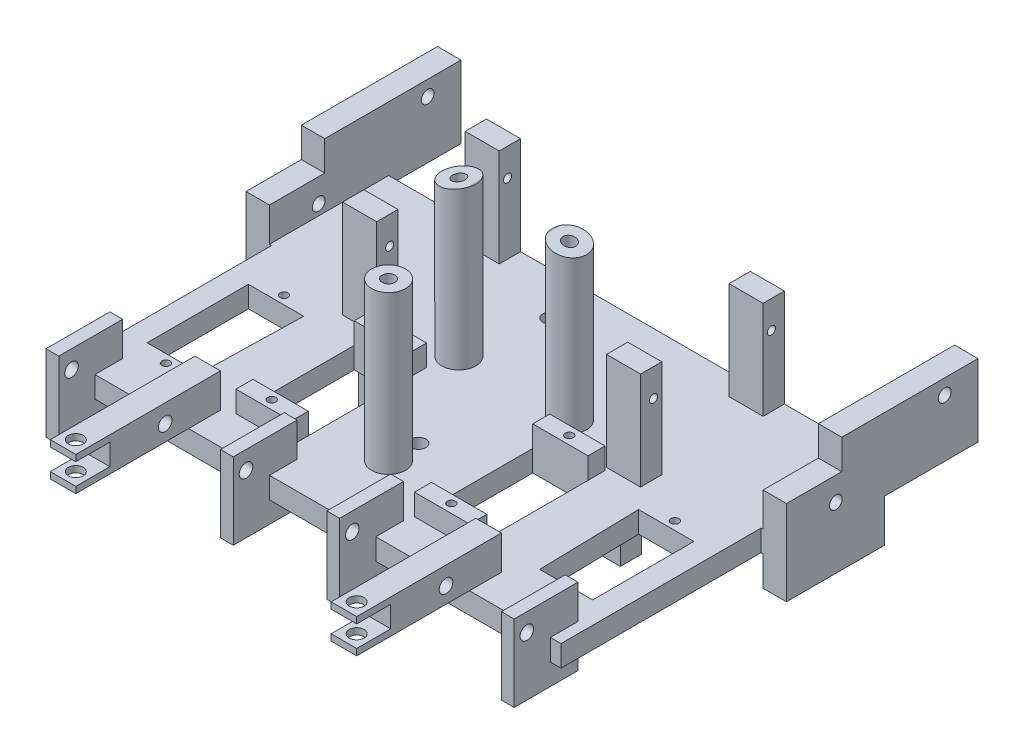
SolidWorks part; units mm, degrees
material "PMMA"
ref_plane "前视基准面" through (0, 0, 0) normal (0, 0, 1) x (1, 0, 0)
ref_plane "上视基准面" through (0, 0, 0) normal (0, 1, 0) x (1, 0, 0)
ref_plane "右视基准面" through (0, 0, 0) normal (1, 0, 0) x (0, 0, -1)
sketch "草图1" plane through (0, 0, 0) normal (0, 1, 0) x (1, 0, 0)
  line L1 (-57.5, 37.5) -> (57.5, 37.5)
  line L2 (-57.5, 37.5) -> (-57.5, -37.5)
  line L3 (-57.5, -37.5) -> (57.5, -37.5)
  line L4 (57.5, 37.5) -> (57.5, -37.5)
  line L5 (-57.5, 37.5) -> (57.5, -37.5) construction
  line L6 (-57.5, -37.5) -> (57.5, 37.5) construction
  point P0 (0, 0)
  dimension "D1" = 115
  dimension "D2" = 75
extrude "凸台-拉伸1" add sketch "草图1" along normal blind 5
sketch "草图4" plane through (0, 5, 0) normal (0, 1, 0) x (1, 0, 0)
  line L1 (-58, 9.5) -> (58, 9.5)
  line L2 (-58, 9.5) -> (-58, 37.5)
  line L3 (-58, 37.5) -> (58, 37.5)
  line L4 (58, 9.5) -> (58, 37.5)
  line L5 (-58, 9.5) -> (58, 37.5) construction
  line L6 (-58, 37.5) -> (58, 9.5) construction
  line L7 (-57.5, -37.5) -> (57.5, -37.5) construction
  point P0 (0, 23.5)
  dimension "D1" = 116
  dimension "D2" = 28
  dimension "D3" = 75
extrude "凸台-拉伸4" add sketch "草图4" against normal blind 5
sketch "草图5" plane through (-58, 0, 0) normal (-1, 0, 0) x (0, 0, 1)
  line L0 (-37.5, 5) -> (-9.5, 5) construction
  line L1 (-9.5, 13) -> (-32.5, 13)
  line L2 (-9.5, 13) -> (-9.5, -7)
  line L3 (-9.5, -7) -> (-32.5, -7)
  line L4 (-32.5, 13) -> (-32.5, -7)
  line L5 (-9.5, 5) -> (-9.5, 0) construction
  dimension "D1" = 8
  dimension "D2" = 23
  dimension "D3" = 20
extrude "凸台-拉伸5" add sketch "草图5" along normal blind 5.5
sketch "草图6" plane through (-58, 0, 0) normal (-1, 0, 0) x (0, 0, 1)
  line L1 (-54.5, 20) -> (-22.5, 20)
  line L2 (-54.5, 20) -> (-54.5, 3)
  line L3 (-54.5, 3) -> (-22.5, 3)
  line L4 (-22.5, 20) -> (-22.5, 3)
  line L5 (-37.5, 5) -> (-32.5, 5) construction
  line L6 (-37.5, 0) -> (-37.5, 5) construction
  dimension "D1" = 15
  dimension "D2" = 17
  dimension "D3" = 32
  dimension "D4" = 17
extrude "凸台-拉伸6" add sketch "草图6" along normal blind 5.5
sketch "草图8" plane through (0, 5, 0) normal (0, 1, 0) x (1, 0, 0)
  line L0 (58, 37.5) -> (-58, 37.5) construction
  line L1 (-35, 37.5) -> (-27, 37.5)
  line L2 (-35, 37.5) -> (-35, 32.5)
  line L3 (-35, 32.5) -> (-27, 32.5)
  line L4 (-27, 37.5) -> (-27, 32.5)
  line L6 (-35, 8.7) -> (-27, 8.7)
  line L7 (-35, 8.7) -> (-35, 3.7)
  line L8 (-35, 3.7) -> (-27, 3.7)
  line L9 (-27, 8.7) -> (-27, 3.7)
  dimension "D1" = 23.8
  dimension "D2" = 35
  dimension "D3" = 8
  dimension "D4" = 5
  dimension "D5" = 5
extrude "凸台-拉伸7" add sketch "草图8" along normal blind 23
sketch "草图9" plane through (0, 5, 0) normal (0, 1, 0) x (1, 0, 0)
  line L1 (-14, -31) -> (-11, -31)
  line L2 (-14, -31) -> (-14, -46)
  line L3 (-14, -46) -> (-11, -46)
  line L4 (-11, -31) -> (-11, -46)
  dimension "D1" = 14
  dimension "D2" = 3
  dimension "D3" = 15
  dimension "D4" = 46
extrude "凸台-拉伸8" add sketch "草图9" along normal blind 8 and the other way blind 10
sketch "草图10" plane through (0, 5, 0) normal (0, 1, 0) x (1, 0, 0)
  line L0 (-14, -31) -> (-14, -46) construction
  line L1 (-55, -31) -> (-52, -31)
  line L2 (-55, -31) -> (-55, -46)
  line L3 (-55, -46) -> (-52, -46)
  line L4 (-52, -31) -> (-52, -46)
  line L6 (-11, -31) -> (-14, -31) construction
  line L7 (-14, -46) -> (-11, -46) construction
  dimension "D1" = 38
extrude "凸台-拉伸9" add sketch "草图10" along normal blind 8 and the other way blind 10
sketch "草图11" plane through (0, 5, 0) normal (0, 1, 0) x (1, 0, 0)
  line L1 (-36, -30) -> (-30, -30)
  line L2 (-36, -30) -> (-36, -64)
  line L3 (-36, -64) -> (-30, -64)
  line L4 (-30, -30) -> (-30, -64)
  dimension "D1" = 6
  dimension "D2" = 34
  dimension "D3" = 64
  dimension "D4" = 30
extrude "凸台-拉伸10" add sketch "草图11" along normal blind 8
sketch "草图12" plane through (0, 5, 0) normal (0, 1, 0) x (1, 0, 0)
  circle A0 centre (-13, 9) radius 4
  dimension "D1" = 13
  dimension "D2" = 9
  dimension "D3" = 8
extrude "凸台-拉伸11" add sketch "草图12" along normal blind 37
sketch "草图19" plane through (-35, 0, 0) normal (-1, 0, 0) x (0, 0, 1)
  line L1 (-8.7, 28) -> (-8.7, 5) construction
  line L2 (-8.7, 28) -> (-3.7, 28) construction
  line L3 (-32.5, 28) -> (-32.5, 5) construction
  circle A0 centre (-6.75, 21.5) radius 0.95
  circle A1 centre (-34.45, 21.5) radius 0.95
  dimension "D1" = 6.5
  dimension "D2" = 1.95
  dimension "D3" = 1.9
  dimension "D4" = 27.7
  dimension "D5" = 1.9
  dimension "D6" = 1.95
extrude "切除-拉伸8" cut sketch "草图19" against normal up to next
sketch "草图25" plane through (0, 5, 0) normal (0, 1, 0) x (1, 0, 0)
  circle A0 centre (0, -20.5) radius 4
  circle A1 centre (-13, 9) radius 4 construction
  dimension "D1" = 20.5
extrude "凸台-拉伸14" add sketch "草图25" along normal blind 37
sketch "草图26" plane through (0, 0, 0) normal (0, 0, 1) x (1, 0, 0)
  line L0 (-17, 42) -> (-17, 40.644)
  line L1 (-17, 42) -> (-17, 5) construction
  line L2 (-17, 40.644) -> (-9.31, 42)
  line L3 (-9, 42) -> (-17, 42) construction
  line L4 (-9.31, 42) -> (-17, 42)
  dimension "D1" = 10
  dimension "D2" = 0.31
extrude "切除-拉伸14" cut sketch "草图26" against normal blind 36
sketch "草图28" plane through (0, 0, 64) normal (0, 0, 1) x (1, 0, 0)
  line L0 (-36, 13) -> (-36, 5) construction
  line L1 (-36, 11.5) -> (-30, 11.5)
  line L2 (-36, 11.5) -> (-36, 6.5)
  line L3 (-36, 6.5) -> (-30, 6.5)
  line L4 (-30, 11.5) -> (-30, 6.5)
  line L5 (-30, 13) -> (-30, 5) construction
  line L6 (-36, 13) -> (-30, 13) construction
  dimension "D1" = 1.5
  dimension "D2" = 5
extrude "切除-拉伸16" cut sketch "草图28" against normal blind 8
sketch "草图29" plane through (0, 13, 0) normal (0, 1, 0) x (1, 0, 0)
  line L0 (-36, -64) -> (-30, -64) construction
  circle A0 centre (-33, -61) radius 1.75
  point P5 (-33, -64)
  dimension "D1" = 3
  dimension "D2" = 3.5
extrude "切除-拉伸17" cut sketch "草图29" against normal blind 8
sketch "草图30" plane through (-55, 0, 0) normal (-1, 0, 0) x (0, 0, 1)
  line L0 (31, 5) -> (37.5, 5) construction
  circle A0 centre (43, 8.75) radius 1.6
  dimension "D1" = 43
  dimension "D2" = 3.75
  dimension "D3" = 3.2
extrude "切除-拉伸18" cut sketch "草图30" against normal blind 48
sketch "草图31" plane through (0, 5, 0) normal (0, 1, 0) x (1, 0, 0)
  circle A0 centre (0, -13.5) radius 1.75
  circle A1 centre (-10, 27.5) radius 1.75
  circle A2 centre (10, 27.5) radius 1.75
  dimension "D1" = 20
  dimension "D2" = 10
  dimension "D3" = 27.5
  dimension "D4" = 3.5
  dimension "D5" = 3.5
  dimension "D7" = 3.5
  dimension "D6" = 13.5
extrude "切除-拉伸19" cut sketch "草图31" against normal blind 20
sketch "草图34" plane through (-55, 0, 0) normal (-1, 0, 0) x (0, 0, 1)
  line L0 (46, -5) -> (46, 13) construction
  line L1 (46, 5) -> (43, 5)
  line L2 (46, 5) -> (46, -5)
  line L3 (46, -5) -> (43, -5)
  line L4 (43, 5) -> (43, -5)
  line L5 (37.5, 5) -> (64, 5) construction
  line L6 (31, -5) -> (46, -5) construction
  dimension "D1" = 3
sketch "草图35" plane through (-63.5, 0, 0) normal (-1, 0, 0) x (0, 0, 1)
  circle A0 centre (-46.6884, 16.4527) radius 1.5
  circle A1 centre (-21.0894, 7.4378) radius 1.5
  dimension "D1" = 3
  dimension "D2" = 3
extrude "切除-拉伸23" cut sketch "草图35" against normal blind 15
sketch "草图36" plane through (0, 5, 0) normal (0, 1, 0) x (1, 0, 0)
  line L0 (-21.1079, 3.9238) -> (-21.1079, -28.1166) construction
  line L1 (-27.473, -1.0985) -> (-14.473, -1.0985)
  line L2 (-27.473, -1.0985) -> (-27.473, -24.8985)
  line L3 (-27.473, -24.8985) -> (-14.473, -24.8985)
  line L4 (-14.473, -1.0985) -> (-14.473, -24.8985)
  line L5 (-39.3368, -1.0985) -> (-39.899, -24.8985)
  line L6 (-45.9718, 4.25) -> (-45.9718, -27.7905) construction
  line L7 (-52.3368, -24.8985) -> (-39.899, -24.8985)
  line L8 (-52.3368, -1.0985) -> (-52.3368, -24.8985)
  line L9 (-52.3368, -1.0985) -> (-39.3368, -1.0985)
  circle A0 centre (-21.1079, 0.8515) radius 0.95
  circle A1 centre (-21.1079, -26.8485) radius 0.95
  circle A2 centre (-45.9718, -26.8485) radius 0.95
  circle A3 centre (-45.9227, 0.8515) radius 0.95
  dimension "D3" = 1.9
  dimension "D4" = 1.9
  dimension "D9" = 1.9
  dimension "D10" = 1.9
  dimension "D1" = 23.8
  dimension "D2" = 13
  dimension "D5" = 1.95
  dimension "D6" = 1.95
  dimension "D7" = 23.8
  dimension "D8" = 13
  dimension "D11" = 1.95
  dimension "D12" = 1.95
extrude "切除-拉伸24" cut sketch "草图36" against normal blind 7
sketch "草图37" plane through (0, 0, 0) normal (0, -1, 0) x (1, 0, 0)
  line L1 (-25.4663, -36.9825) -> (-31.4663, -36.9825)
  line L2 (-25.4663, -36.9825) -> (-25.4663, -31.9825)
  line L3 (-25.4663, -31.9825) -> (-31.4663, -31.9825)
  line L4 (-31.4663, -36.9825) -> (-31.4663, -31.9825)
  line L5 (-25.4663, -8.1825) -> (-30.7728, -8.1825)
  line L6 (-25.4663, -8.1825) -> (-25.4663, -3.1825)
  line L7 (-25.4663, -3.1825) -> (-30.7728, -3.1825)
  line L8 (-30.7728, -8.1825) -> (-30.7728, -3.1825)
  dimension "D1" = 23.8
  dimension "D2" = 6
  dimension "D3" = 5
  dimension "D4" = 5
extrude "凸台-拉伸15" add sketch "草图37" along normal blind 13
sketch "草图38" plane through (-31.4663, 0, 0) normal (-1, 0, 0) x (0, 0, 1)
  line L0 (-31.9825, -13) -> (-31.9825, 0) construction
  line L2 (-37.5, 0) -> (-32.5, 0) construction
  line L3 (-20.0825, 2.1642) -> (-20.0825, -15.8009) construction
  circle A0 centre (-33.9325, -4.5) radius 0.95
  circle A1 centre (-6.2325, -4.5) radius 0.95
  dimension "D1" = 1.9
  dimension "D2" = 1.95
  dimension "D3" = 4.5
  dimension "D4" = 11.9
extrude "切除-拉伸25" cut sketch "草图38" against normal blind 13
sketch "草图43" plane through (0, 0, 0) normal (0, -1, 0) x (1, 0, 0)
  line L0 (58, -37.5) -> (-58, -37.5) construction
  line L1 (-54.7728, -1.1825) -> (-17.4663, -1.1825)
  line L2 (-54.7728, -1.1825) -> (-54.7728, -37.5)
  line L3 (-54.7728, -37.5) -> (-17.4663, -37.5)
  line L4 (-17.4663, -1.1825) -> (-17.4663, -37.5)
  line L5 (-25.4663, -3.1825) -> (-30.7728, -3.1825) construction
  line L6 (-25.4663, -8.1825) -> (-25.4663, -3.1825) construction
  line L7 (-25.4663, -3.1825) -> (-30.7728, -3.1825) construction
  line L8 (-30.7728, -3.1825) -> (-30.7728, -8.1825) construction
  line L9 (-30.7728, -8.1825) -> (-25.4663, -8.1825) construction
  line L10 (-25.4663, -36.9825) -> (-25.4663, -31.9825) construction
  line L11 (-25.4663, -31.9825) -> (-31.4663, -31.9825) construction
  line L12 (-31.4663, -31.9825) -> (-31.4663, -36.9825) construction
  line L13 (-31.4663, -36.9825) -> (-25.4663, -36.9825) construction
  line L14 (-25.4663, -8.1825) -> (-25.4663, -3.1825)
  line L15 (-25.4663, -3.1825) -> (-30.7728, -3.1825)
  line L16 (-30.7728, -3.1825) -> (-30.7728, -8.1825)
  line L17 (-30.7728, -8.1825) -> (-25.4663, -8.1825)
  line L18 (-25.4663, -36.9825) -> (-25.4663, -31.9825)
  line L19 (-25.4663, -31.9825) -> (-31.4663, -31.9825)
  line L20 (-31.4663, -31.9825) -> (-31.4663, -36.9825)
  line L21 (-31.4663, -36.9825) -> (-25.4663, -36.9825)
  dimension "D1" = 2
  dimension "D2" = 8
  dimension "D3" = 24
extrude "切除-拉伸28" cut sketch "草图43" against normal blind 2
sketch "草图41" plane through (0, 5, 0) normal (0, 1, 0) x (1, 0, 0)
  line L0 (-27.473, -1.0985) -> (-27.473, -24.8985) construction
  line L1 (-14.473, -1.0985) -> (-27.473, -1.0985)
  line L2 (-14.473, -1.0985) -> (-14.473, 2.9015)
  line L3 (-14.473, 2.9015) -> (-27.473, 2.9015)
  line L4 (-27.473, -1.0985) -> (-27.473, 2.9015)
  line L5 (-14.473, -24.8985) -> (-14.473, -1.0985) construction
  line L6 (-27.473, -24.8985) -> (-14.473, -24.8985)
  line L7 (-27.473, -24.8985) -> (-27.473, -28.8985)
  line L8 (-27.473, -28.8985) -> (-14.473, -28.8985)
  line L9 (-14.473, -24.8985) -> (-14.473, -28.8985)
  circle A0 centre (-21.1079, 0.8515) radius 0.95
  circle A1 centre (-21.1079, -26.8485) radius 0.95
  dimension "D3" = 1.9
  dimension "D4" = 1.9
  dimension "D1" = 4
  dimension "D2" = 4
extrude "凸台-拉伸16" add sketch "草图41" along normal blind 5
sketch "草图39" plane through (0, 5, 0) normal (0, 1, 0) x (1, 0, 0)
  circle A0 centre (-13, 9) radius 1.5
  circle A1 centre (0, -20.5) radius 1.5
  dimension "D1" = 3
  dimension "D2" = 3
extrude "切除-拉伸26" cut sketch "草图39" against normal blind 13 and the other way blind 42
mirror "镜向1" about plane through (0, 0, 0) normal (1, 0, 0) of "凸台-拉伸16", "切除-拉伸26", "切除-拉伸25", "凸台-拉伸15", "切除-拉伸24", "切除-拉伸23", "切除-拉伸19", "切除-拉伸18", "切除-拉伸17", "切除-拉伸16", "切除-拉伸14", "凸台-拉伸14", "切除-拉伸8", "凸台-拉伸11", "凸台-拉伸10", "凸台-拉伸9", "凸台-拉伸8", "凸台-拉伸7", "凸台-拉伸6", "凸台-拉伸5", "切除-拉伸28"
